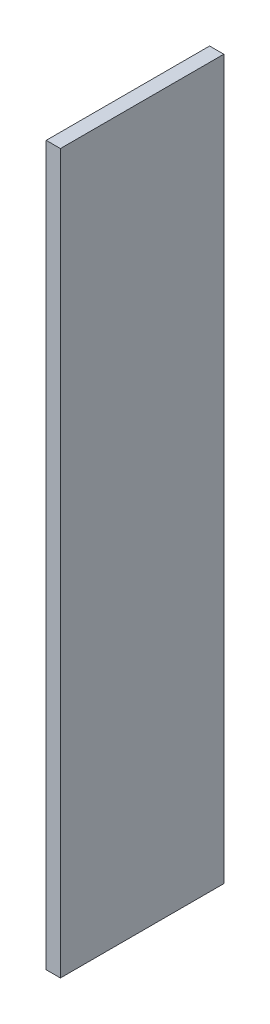
SolidWorks part; units mm, degrees
material "Glass"
ref_plane "Front" through (0, 0, 0) normal (0, 0, 1) x (1, 0, 0)
ref_plane "Top" through (0, 0, 0) normal (0, 1, 0) x (1, 0, 0)
ref_plane "Right" through (0, 0, 0) normal (1, 0, 0) x (0, 0, -1)
sketch "Sketch1" plane through (0, 0, 0) normal (0, 1, 0) x (1, 0, 0)
  line L1 (-50.8, 584.2) -> (50.8, 584.2)
  line L2 (-50.8, 584.2) -> (-50.8, -584.2)
  line L3 (-50.8, -584.2) -> (50.8, -584.2)
  line L4 (50.8, 584.2) -> (50.8, -584.2)
  line L5 (-50.8, 584.2) -> (50.8, -584.2) construction
  line L6 (-50.8, -584.2) -> (50.8, 584.2) construction
  point P0 (0, 0)
  dimension "D1" = 101.6
  dimension "D2" = 1168.4
extrude "Boss-Extrude1" add sketch "Sketch1" along normal blind 5137.15
